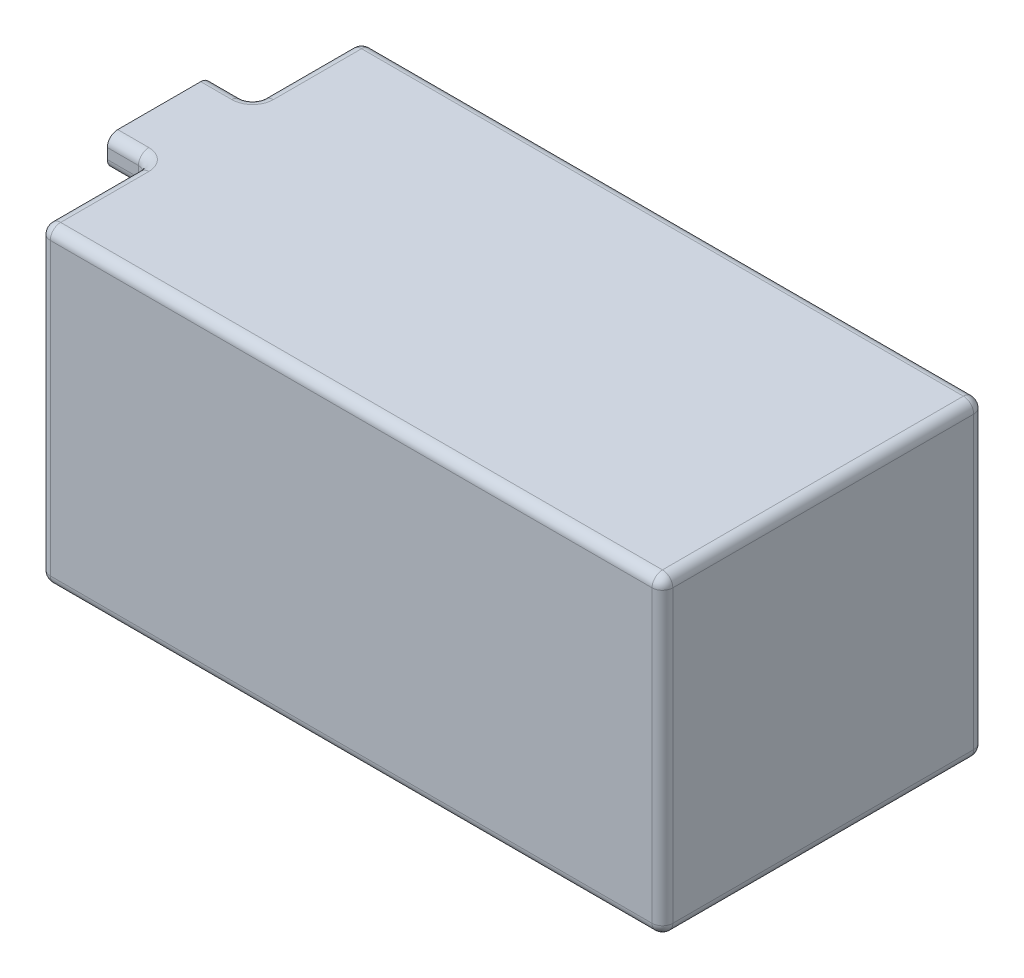
SolidWorks part; units mm, degrees
ref_plane "Front Plane" through (0, 0, 0) normal (0, 0, 1) x (1, 0, 0)
ref_plane "Top Plane" through (0, 0, 0) normal (0, 1, 0) x (1, 0, 0)
ref_plane "Right Plane" through (0, 0, 0) normal (1, 0, 0) x (0, 0, -1)
sketch "Sketch1" plane through (0, 0, 0) normal (0, 1, 0) x (1, 0, 0)
  line L1 (-38.1, -19.685) -> (38.1, -19.685)
  line L2 (-38.1, -19.685) -> (-38.1, 19.685)
  line L3 (-38.1, 19.685) -> (38.1, 19.685)
  line L4 (38.1, -19.685) -> (38.1, 19.685)
  line L5 (-38.1, -19.685) -> (38.1, 19.685) construction
  line L6 (-38.1, 19.685) -> (38.1, -19.685) construction
  point P0 (0, 0)
  dimension "D1" = 76.2
  dimension "D2" = 39.37
extrude "Boss-Extrude1" add sketch "Sketch1" along normal blind 38.1
sketch "Sketch2" plane through (-38.1, 0, 0) normal (-1, 0, 0) x (0, 0, 1)
  line L0 (-19.685, 38.1) -> (19.685, 38.1) construction
  line L1 (-6.35, 38.1) -> (6.35, 38.1)
  line L2 (-6.35, 38.1) -> (-6.35, 34.29)
  line L3 (-6.35, 34.29) -> (6.35, 34.29)
  line L4 (6.35, 38.1) -> (6.35, 34.29)
  dimension "D1" = 12.7
  dimension "D2" = 6.35
  dimension "D3" = 3.81
extrude "Boss-Extrude2" add sketch "Sketch2" along normal blind 5.08
fillet "Fillet1" radius 1.27 20 edges at (-40.64, 38.1, 6.35) (-40.64, 38.1, -6.35) (-38.1, 34.29, 0) (-38.1, 36.195, 6.35) (-38.1, 38.1, 13.0175) (-38.1, 38.1, -13.0175) (-38.1, 36.195, -6.35) (-38.1, 0, 0) (38.1, 0, 0) (38.1, 38.1, 0) (-38.1, 19.05, 19.685) (0, 0, 19.685) (0, 38.1, 19.685) (38.1, 19.05, 19.685) (38.1, 19.05, -19.685) (0, 0, -19.685) (0, 38.1, -19.685) (-38.1, 19.05, -19.685) (-40.64, 34.29, -6.35) (-40.64, 34.29, 6.35)
